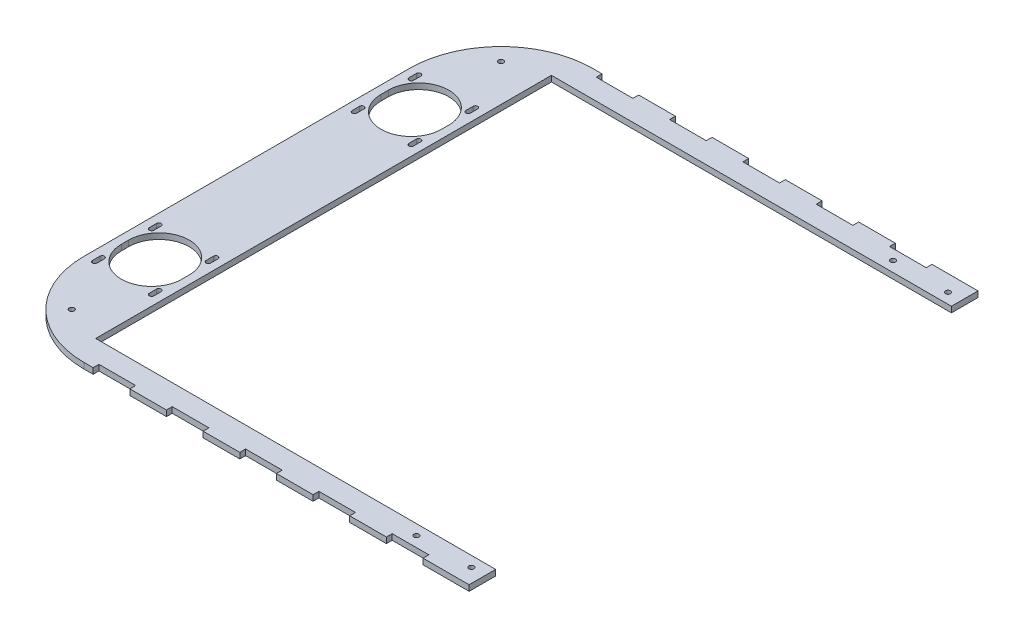
SolidWorks part; units mm, degrees
ref_plane "Front Plane" through (0, 0, 0) normal (0, 0, 1) x (1, 0, 0)
ref_plane "Top Plane" through (0, 0, 0) normal (0, 1, 0) x (1, 0, 0)
ref_plane "Right Plane" through (0, 0, 0) normal (1, 0, 0) x (0, 0, -1)
sketch "Sketch1" plane through (0, 11.0302, 0) normal (0, 1, 0) x (1, 0, 0)
  line L0 (-162.1567, -108.1674) -> (-194.8999, -108.1674) construction
  line L1 (-194.8999, 71.4826) -> (-162.1567, 71.4826) construction
  line L2 (-199.5283, 34.111) -> (-199.5283, 66.8542) construction
  line L3 (-157.5283, -142.1674) -> (-157.5283, 105.4826) construction
  line L4 (-162.1567, -108.1674) -> (-194.8999, -108.1674)
  line L5 (-194.8999, 71.4826) -> (-162.1567, 71.4826)
  line L6 (-199.5283, 34.111) -> (-199.5283, 66.8542)
  line L7 (-157.5283, -108.1674) -> (-157.5283, 71.4826)
  line L8 (-162.1567, 71.4826) -> (-157.5283, 71.4826)
  line L9 (-162.1567, -108.1674) -> (-157.5283, -108.1674)
  line L10 (-199.5283, 34.111) -> (-199.5283, -108.1674)
  line L11 (-199.5283, -108.1674) -> (-194.8999, -108.1674)
  line L12 (-194.8999, 71.4826) -> (-199.5283, 71.4826)
  line L13 (-199.5283, 66.8542) -> (-199.5283, 71.4826)
  circle A0 centre (-163.0283, 65.9826) radius 1.25 construction
  circle A1 centre (-163.0283, 34.9826) radius 1.25 construction
  circle A2 centre (-194.0283, 34.9826) radius 1.25 construction
  circle A3 centre (-194.0283, 65.9826) radius 1.25 construction
  circle A4 centre (-163.0283, -102.6674) radius 1.25 construction
  circle A5 centre (-163.0283, -71.6674) radius 1.25 construction
  circle A6 centre (-194.0283, -102.6674) radius 1.25 construction
  circle A7 centre (-194.0283, -71.6674) radius 1.25 construction
  circle A8 centre (-163.0283, 65.9826) radius 1.25
  circle A9 centre (-163.0283, 34.9826) radius 1.25
  circle A10 centre (-194.0283, 34.9826) radius 1.25
  circle A11 centre (-194.0283, 65.9826) radius 1.25
  circle A12 centre (-163.0283, -102.6674) radius 1.25
  circle A13 centre (-163.0283, -71.6674) radius 1.25
  circle A14 centre (-194.0283, -102.6674) radius 1.25
  circle A15 centre (-194.0283, -71.6674) radius 1.25
  circle A16 centre (-178.5283, -87.1674) radius 16.5 construction
  circle A17 centre (-178.5283, 50.4826) radius 16.5 construction
  circle A18 centre (-178.5283, -87.1674) radius 16.5
  circle A19 centre (-178.5283, 50.4826) radius 16.5
extrude "Boss-Extrude1" add sketch "Sketch1" along normal blind 3.15
sketch "Sketch2" plane through (0, 14.1802, 0) normal (0, 1, 0) x (1, 0, 0)
  line L0 (-157.5283, -142.1674) -> (-157.5283, 105.4826) construction
  line L1 (-157.5283, -142.1674) -> (-157.5283, 105.4826)
  line L2 (45.6717, -142.1674) -> (-157.5283, -142.1674) construction
  line L3 (45.6717, -142.1674) -> (-157.5283, -142.1674)
  line L4 (45.6717, 105.4826) -> (45.6717, -142.1674) construction
  line L5 (45.6717, 105.4826) -> (45.6717, -142.1674)
  line L6 (-157.5283, 105.4826) -> (45.6717, 105.4826) construction
  line L7 (-157.5283, 105.4826) -> (45.6717, 105.4826)
  line L8 (-199.5283, 71.4826) -> (-199.5283, -108.1674) construction
  line L9 (-199.5283, 71.4826) -> (-199.5283, -108.1674)
  line L10 (-199.5283, 71.4826) -> (-199.5283, 105.4826)
  line L11 (-199.5283, 105.4826) -> (-157.5283, 105.4826)
  line L12 (-199.5283, -108.1674) -> (-199.5283, -142.1674)
  line L13 (-199.5283, 120.4826) -> (-157.5283, 120.4826)
  line L14 (-157.5283, 120.4826) -> (60.6717, 120.4826)
  line L15 (60.6717, 120.4826) -> (60.6717, -157.1674)
  line L16 (60.6717, -157.1674) -> (-157.5283, -157.1674)
  line L17 (-157.5283, 107.4826) -> (45.6717, 107.4826)
  line L18 (45.6717, -144.1674) -> (-157.5283, -144.1674)
  line L19 (-157.5283, 105.4826) -> (-157.5283, 107.4826)
  line L20 (45.6717, 105.4826) -> (45.6717, 107.4826)
  line L21 (45.6717, -142.1674) -> (45.6717, -144.1674)
  line L22 (-157.5283, -142.1674) -> (-157.5283, -144.1674)
  line L23 (45.6717, 107.4826) -> (60.6717, 107.4826)
  line L24 (45.6717, -144.1674) -> (60.6717, -144.1674)
  line L25 (-157.5283, -157.1674) -> (-199.5283, -157.1674)
  line L26 (-199.5283, -157.1674) -> (-199.5283, -142.1674)
  line L27 (-199.5283, 120.4826) -> (-199.5283, 105.4826)
  line M10 (-199.5283, -108.1674) -> (-157.5283, -108.1674)
  line M12 (-157.5283, 71.4826) -> (-199.5283, 71.4826)
  dimension "D1" = 15
  dimension "D2" = 2
extrude "Boss-Extrude2" add sketch "Sketch2" against normal up to surface (3.15 mm away) contours L26 L25 L16 L15 L24 L18 L22 L1 L12 M10 | L11 L10 L1 M12 | L13 L27 L11 L19 L17 L23 L15 L14 up to face at (-178.5283, 11.0302, 18.3424)
fillet "Fillet1" radius 50 2 edges at (-199.5283, 12.6052, 157.1674) (-199.5283, 12.6052, -120.4826)
sketch "Sketch3" plane through (0, 14.1802, 0) normal (0, 1, 0) x (1, 0, 0)
  line L0 (55.5717, 120.4826) -> (-144.4283, 120.4826) construction
  line L1 (-104.4283, 120.4826) -> (-84.4283, 120.4826)
  line L2 (-144.4283, 120.4826) -> (-124.4283, 120.4826)
  line L3 (-144.4283, 120.4826) -> (-144.4283, 117.3226)
  line L4 (-144.4283, 117.3226) -> (-124.4283, 117.3226)
  line L5 (-124.4283, 120.4826) -> (-124.4283, 117.3226)
  line L6 (-144.4283, 120.4826) -> (-124.4283, 117.3226) construction
  line L7 (-144.4283, 117.3226) -> (-124.4283, 120.4826) construction
  line L8 (-84.4283, 120.4826) -> (-84.4283, 117.3226)
  line L9 (-104.4283, 117.3226) -> (-84.4283, 117.3226)
  line L10 (-104.4283, 120.4826) -> (-104.4283, 117.3226)
  line L11 (-64.4283, 120.4826) -> (-44.4283, 120.4826)
  line L12 (-44.4283, 120.4826) -> (-44.4283, 117.3226)
  line L13 (-64.4283, 117.3226) -> (-44.4283, 117.3226)
  line L14 (-64.4283, 120.4826) -> (-64.4283, 117.3226)
  line L15 (-24.4283, 120.4826) -> (-4.4283, 120.4826)
  line L16 (-4.4283, 120.4826) -> (-4.4283, 117.3226)
  line L17 (-24.4283, 117.3226) -> (-4.4283, 117.3226)
  line L18 (-24.4283, 120.4826) -> (-24.4283, 117.3226)
  line L19 (15.5717, 120.4826) -> (35.5717, 120.4826)
  line L20 (35.5717, 120.4826) -> (35.5717, 117.3226)
  line L21 (15.5717, 117.3226) -> (35.5717, 117.3226)
  line L22 (15.5717, 120.4826) -> (15.5717, 117.3226)
  line L23 (-199.5283, -18.3424) -> (55.5717, -18.3424) construction
  line L24 (-199.5283, 70.4826) -> (-199.5283, -107.1674) construction
  line L25 (15.5717, -157.1674) -> (15.5717, -154.0074)
  line L26 (-24.4283, -157.1674) -> (-24.4283, -154.0074)
  line L27 (-64.4283, -157.1674) -> (-64.4283, -154.0074)
  line L28 (-104.4283, -157.1674) -> (-104.4283, -154.0074)
  line L29 (-144.4283, -154.0074) -> (-124.4283, -157.1674) construction
  line L30 (-144.4283, -157.1674) -> (-124.4283, -154.0074) construction
  line L31 (-144.4283, -157.1674) -> (-144.4283, -154.0074)
  line L32 (55.5717, -157.1674) -> (-144.4283, -157.1674) construction
  line L33 (15.5717, -154.0074) -> (35.5717, -154.0074)
  line L34 (35.5717, -157.1674) -> (35.5717, -154.0074)
  line L35 (15.5717, -157.1674) -> (35.5717, -157.1674)
  line L36 (-24.4283, -154.0074) -> (-4.4283, -154.0074)
  line L37 (-4.4283, -157.1674) -> (-4.4283, -154.0074)
  line L38 (-24.4283, -157.1674) -> (-4.4283, -157.1674)
  line L39 (-64.4283, -154.0074) -> (-44.4283, -154.0074)
  line L40 (-44.4283, -157.1674) -> (-44.4283, -154.0074)
  line L41 (-64.4283, -157.1674) -> (-44.4283, -157.1674)
  line L42 (-104.4283, -154.0074) -> (-84.4283, -154.0074)
  line L43 (-84.4283, -157.1674) -> (-84.4283, -154.0074)
  line L44 (-124.4283, -157.1674) -> (-124.4283, -154.0074)
  line L45 (-144.4283, -154.0074) -> (-124.4283, -154.0074)
  line L46 (-144.4283, -157.1674) -> (-124.4283, -157.1674)
  line L47 (-104.4283, -157.1674) -> (-84.4283, -157.1674)
  point P7 (-134.4283, 118.9026)
  point P49 (-134.4283, -155.5874)
  dimension "D1" = 20
  dimension "D2" = 3.16
  dimension "D3" = 5
extrude "Cut-Extrude1" cut sketch "Sketch3" against normal through all
sketch "Sketch4" plane through (0, 14.1802, 0) normal (0, 1, 0) x (1, 0, 0)
  line L0 (-157.5283, -18.3424) -> (-199.5283, -18.3424) construction
  line L1 (-157.5283, -144.1674) -> (-157.5283, 107.4826) construction
  line L2 (-199.5283, 70.4826) -> (-199.5283, -107.1674) construction
  line L3 (-157.5283, 78.4826) -> (-184.8836, 105.838) construction
  line L4 (-157.5283, -144.1674) -> (-157.5283, 107.4826) construction
  circle A0 centre (-177.8126, 98.7669) radius 1.4
  circle A1 centre (-177.8126, -135.4517) radius 1.4
  dimension "D1" = 10
extrude "Cut-Extrude2" cut sketch "Sketch4" against normal blind 10
sketch "Sketch5" plane through (0, 14.1802, 0) normal (0, 1, 0) x (1, 0, 0)
  circle A1 centre (53.1217, -148.3424) radius 1.4 construction
  circle A2 centre (53.1217, 111.6476) radius 1.4
  circle A3 centre (53.1217, -148.3424) radius 1.4
  circle A5 centre (23.1217, 111.6476) radius 1.4
  circle A6 centre (23.1217, -148.3424) radius 1.4 construction
  circle A7 centre (23.1217, -148.3424) radius 1.4
  circle A10 centre (53.1217, 111.6476) radius 1.4 construction
  circle A11 centre (23.1217, 111.6476) radius 1.4 construction
extrude "Cut-Extrude3" cut sketch "Sketch5" against normal blind 10
sketch "Sketch6" plane through (0, 14.1802, 0) normal (0, 1, 0) x (1, 0, 0)
  line L0 (-161.7783, 69.9826) -> (-161.7783, 65.9826)
  line L1 (-164.2783, 65.9826) -> (-164.2783, 69.9826)
  line L2 (-161.7783, 38.9826) -> (-161.7783, 34.9826)
  line L3 (-164.2783, 34.9826) -> (-164.2783, 38.9826)
  line L4 (-192.7783, 38.9826) -> (-192.7783, 34.9826)
  line L5 (-195.2783, 34.9826) -> (-195.2783, 38.9826)
  line L6 (-195.2783, 69.9826) -> (-195.2783, 65.9826)
  line L7 (-192.7783, 69.9826) -> (-192.7783, 65.9826)
  line L8 (-162.0283, 54.4826) -> (-162.0283, 50.4826)
  line L9 (-195.0283, 54.4826) -> (-195.0283, 50.4826)
  line L10 (-157.5283, -18.3424) -> (-199.5283, -18.3424) construction
  line L11 (-195.0283, -91.1674) -> (-195.0283, -87.1674)
  line L12 (-162.0283, -91.1674) -> (-162.0283, -87.1674)
  line L13 (-192.7783, -106.6674) -> (-192.7783, -102.6674)
  line L14 (-195.2783, -106.6674) -> (-195.2783, -102.6674)
  line L15 (-195.2783, -71.6674) -> (-195.2783, -75.6674)
  line L16 (-192.7783, -75.6674) -> (-192.7783, -71.6674)
  line L17 (-164.2783, -71.6674) -> (-164.2783, -75.6674)
  line L18 (-161.7783, -75.6674) -> (-161.7783, -71.6674)
  line L19 (-164.2783, -102.6674) -> (-164.2783, -106.6674)
  line L20 (-161.7783, -106.6674) -> (-161.7783, -102.6674)
  line L48 (-104.4283, 117.3226) -> (-104.4283, 120.4826)
  line L49 (-104.4283, 120.4826) -> (-124.4283, 120.4826)
  line L50 (-124.4283, 120.4826) -> (-124.4283, 117.3226)
  line L51 (-124.4283, 117.3226) -> (-144.4283, 117.3226)
  line L52 (-144.4283, 117.3226) -> (-144.4283, 120.4826)
  line L53 (-144.4283, 120.4826) -> (-149.5283, 120.4826)
  line L54 (-199.5283, 70.4826) -> (-199.5283, -107.1674)
  line L55 (-149.5283, -157.1674) -> (-144.4283, -157.1674)
  line L56 (-144.4283, -157.1674) -> (-144.4283, -154.0074)
  line L57 (-144.4283, -154.0074) -> (-124.4283, -154.0074)
  line L58 (-124.4283, -154.0074) -> (-124.4283, -157.1674)
  line L59 (-124.4283, -157.1674) -> (-104.4283, -157.1674)
  line L60 (-104.4283, -157.1674) -> (-104.4283, -154.0074)
  line L61 (-104.4283, -154.0074) -> (-84.4283, -154.0074)
  line L62 (-84.4283, -154.0074) -> (-84.4283, -157.1674)
  line L63 (-84.4283, -157.1674) -> (-64.4283, -157.1674)
  line L64 (-64.4283, -157.1674) -> (-64.4283, -154.0074)
  line L65 (-64.4283, -154.0074) -> (-44.4283, -154.0074)
  line L66 (-44.4283, -154.0074) -> (-44.4283, -157.1674)
  line L67 (-44.4283, -157.1674) -> (-24.4283, -157.1674)
  line L68 (-24.4283, -157.1674) -> (-24.4283, -154.0074)
  line L69 (-24.4283, -154.0074) -> (-4.4283, -154.0074)
  line L70 (-4.4283, -154.0074) -> (-4.4283, -157.1674)
  line L71 (-4.4283, -157.1674) -> (15.5717, -157.1674)
  line L72 (15.5717, -157.1674) -> (15.5717, -154.0074)
  line L73 (15.5717, -154.0074) -> (35.5717, -154.0074)
  line L74 (35.5717, -154.0074) -> (35.5717, -157.1674)
  line L75 (35.5717, -157.1674) -> (60.6717, -157.1674)
  line L76 (60.6717, -157.1674) -> (60.6717, -144.1674)
  line L77 (60.6717, -144.1674) -> (-157.5283, -144.1674)
  line L78 (-157.5283, -144.1674) -> (-157.5283, 107.4826)
  line L79 (-157.5283, 107.4826) -> (60.6717, 107.4826)
  line L80 (60.6717, 107.4826) -> (60.6717, 120.4826)
  line L81 (60.6717, 120.4826) -> (35.5717, 120.4826)
  line L82 (35.5717, 120.4826) -> (35.5717, 117.3226)
  line L83 (35.5717, 117.3226) -> (15.5717, 117.3226)
  line L84 (15.5717, 117.3226) -> (15.5717, 120.4826)
  line L85 (15.5717, 120.4826) -> (-4.4283, 120.4826)
  line L86 (-4.4283, 120.4826) -> (-4.4283, 117.3226)
  line L87 (-4.4283, 117.3226) -> (-24.4283, 117.3226)
  line L88 (-24.4283, 117.3226) -> (-24.4283, 120.4826)
  line L89 (-24.4283, 120.4826) -> (-44.4283, 120.4826)
  line L90 (-44.4283, 120.4826) -> (-44.4283, 117.3226)
  line L91 (-44.4283, 117.3226) -> (-64.4283, 117.3226)
  line L92 (-64.4283, 117.3226) -> (-64.4283, 120.4826)
  line L93 (-64.4283, 120.4826) -> (-84.4283, 120.4826)
  line L94 (-84.4283, 120.4826) -> (-84.4283, 117.3226)
  line L95 (-84.4283, 117.3226) -> (-104.4283, 117.3226)
  line L96 (-104.4283, 117.3226) -> (-104.4283, 120.4826)
  line L97 (-104.4283, 120.4826) -> (-124.4283, 120.4826)
  line L98 (-124.4283, 120.4826) -> (-124.4283, 117.3226)
  line L99 (-124.4283, 117.3226) -> (-144.4283, 117.3226)
  line L100 (-144.4283, 117.3226) -> (-144.4283, 120.4826)
  line L101 (-144.4283, 120.4826) -> (-149.5283, 120.4826)
  line L102 (-199.5283, 70.4826) -> (-199.5283, -107.1674)
  line L103 (-149.5283, -157.1674) -> (-144.4283, -157.1674)
  line L104 (-144.4283, -157.1674) -> (-144.4283, -154.0074)
  line L105 (-144.4283, -154.0074) -> (-124.4283, -154.0074)
  line L106 (-124.4283, -154.0074) -> (-124.4283, -157.1674)
  line L107 (-124.4283, -157.1674) -> (-104.4283, -157.1674)
  line L108 (-104.4283, -157.1674) -> (-104.4283, -154.0074)
  line L109 (-104.4283, -154.0074) -> (-84.4283, -154.0074)
  line L110 (-84.4283, -154.0074) -> (-84.4283, -157.1674)
  line L111 (-84.4283, -157.1674) -> (-64.4283, -157.1674)
  line L112 (-64.4283, -157.1674) -> (-64.4283, -154.0074)
  line L113 (-64.4283, -154.0074) -> (-44.4283, -154.0074)
  line L114 (-44.4283, -154.0074) -> (-44.4283, -157.1674)
  line L115 (-44.4283, -157.1674) -> (-24.4283, -157.1674)
  line L116 (-24.4283, -157.1674) -> (-24.4283, -154.0074)
  line L117 (-24.4283, -154.0074) -> (-4.4283, -154.0074)
  line L118 (-4.4283, -154.0074) -> (-4.4283, -157.1674)
  line L119 (-4.4283, -157.1674) -> (15.5717, -157.1674)
  line L120 (15.5717, -157.1674) -> (15.5717, -154.0074)
  line L121 (15.5717, -154.0074) -> (35.5717, -154.0074)
  line L122 (35.5717, -154.0074) -> (35.5717, -157.1674)
  line L123 (35.5717, -157.1674) -> (60.6717, -157.1674)
  line L124 (60.6717, -157.1674) -> (60.6717, -144.1674)
  line L125 (60.6717, -144.1674) -> (-157.5283, -144.1674)
  line L126 (-157.5283, -144.1674) -> (-157.5283, 107.4826)
  line L127 (-157.5283, 107.4826) -> (60.6717, 107.4826)
  line L128 (60.6717, 107.4826) -> (60.6717, 120.4826)
  line L129 (60.6717, 120.4826) -> (35.5717, 120.4826)
  line L130 (35.5717, 120.4826) -> (35.5717, 117.3226)
  line L131 (35.5717, 117.3226) -> (15.5717, 117.3226)
  line L132 (15.5717, 117.3226) -> (15.5717, 120.4826)
  line L133 (15.5717, 120.4826) -> (-4.4283, 120.4826)
  line L134 (-4.4283, 120.4826) -> (-4.4283, 117.3226)
  line L135 (-4.4283, 117.3226) -> (-24.4283, 117.3226)
  line L136 (-24.4283, 117.3226) -> (-24.4283, 120.4826)
  line L137 (-24.4283, 120.4826) -> (-44.4283, 120.4826)
  line L138 (-44.4283, 120.4826) -> (-44.4283, 117.3226)
  line L139 (-44.4283, 117.3226) -> (-64.4283, 117.3226)
  line L140 (-64.4283, 117.3226) -> (-64.4283, 120.4826)
  line L141 (-64.4283, 120.4826) -> (-84.4283, 120.4826)
  line L142 (-84.4283, 120.4826) -> (-84.4283, 117.3226)
  line L143 (-84.4283, 117.3226) -> (-104.4283, 117.3226)
  arc A0 (-195.2783, 65.9826) -> (-192.7783, 65.9826) centre (-194.0283, 65.9826) ccw
  arc A2 (-149.5283, 120.4826) -> (-199.5283, 70.4826) centre (-149.5283, 70.4826) ccw
  arc A3 (-199.5283, -107.1674) -> (-149.5283, -157.1674) centre (-149.5283, -107.1674) ccw
  arc A4 (-149.5283, 120.4826) -> (-199.5283, 70.4826) centre (-149.5283, 70.4826) ccw
  arc A5 (-199.5283, -107.1674) -> (-149.5283, -157.1674) centre (-149.5283, -107.1674) ccw
  arc A6 (-162.0283, 54.4826) -> (-195.0283, 54.4826) centre (-178.5283, 54.4826) ccw
  arc A7 (-195.2783, -71.6674) -> (-192.7783, -71.6674) centre (-194.0283, -71.6674) cw
  arc A8 (-164.2783, -71.6674) -> (-161.7783, -71.6674) centre (-163.0283, -71.6674) cw
  arc A9 (-164.2783, -102.6674) -> (-161.7783, -102.6674) centre (-163.0283, -102.6674) cw
  arc A10 (-195.0283, -87.1674) -> (-162.0283, -87.1674) centre (-178.5283, -87.1674) cw
  arc A12 (-192.7783, 69.9826) -> (-195.2783, 69.9826) centre (-194.0283, 69.9826) ccw
  arc A14 (-161.7783, 38.9826) -> (-164.2783, 38.9826) centre (-163.0283, 38.9826) ccw
  arc A16 (-161.7783, 69.9826) -> (-164.2783, 69.9826) centre (-163.0283, 69.9826) ccw
  arc A18 (-192.7783, 38.9826) -> (-195.2783, 38.9826) centre (-194.0283, 38.9826) ccw
  arc A19 (-192.7783, -75.6674) -> (-195.2783, -75.6674) centre (-194.0283, -75.6674) cw
  arc A20 (-161.7783, -106.6674) -> (-164.2783, -106.6674) centre (-163.0283, -106.6674) cw
  arc A21 (-161.7783, -75.6674) -> (-164.2783, -75.6674) centre (-163.0283, -75.6674) cw
  arc A22 (-192.7783, -106.6674) -> (-195.2783, -106.6674) centre (-194.0283, -106.6674) cw
  arc A23 (-162.0283, -91.1674) -> (-195.0283, -91.1674) centre (-178.5283, -91.1674) cw
  arc A24 (-195.2783, -102.6674) -> (-192.7783, -102.6674) centre (-194.0283, -102.6674) cw
  circle A25 centre (-177.8126, 98.7669) radius 1.4
  circle A26 centre (-177.8126, 98.7669) radius 1.4
  circle A27 centre (-177.8126, -135.4517) radius 1.4
  circle A28 centre (-177.8126, -135.4517) radius 1.4
  circle A29 centre (53.1217, 111.6476) radius 1.4
  circle A30 centre (53.1217, 111.6476) radius 1.4
  circle A31 centre (53.1217, -148.3424) radius 1.4
  circle A32 centre (53.1217, -148.3424) radius 1.4
  arc A33 (-195.0283, 50.4826) -> (-162.0283, 50.4826) centre (-178.5283, 50.4826) ccw
  arc A34 (-164.2783, 65.9826) -> (-161.7783, 65.9826) centre (-163.0283, 65.9826) ccw
  arc A35 (-164.2783, 34.9826) -> (-161.7783, 34.9826) centre (-163.0283, 34.9826) ccw
  arc A36 (-195.2783, 34.9826) -> (-192.7783, 34.9826) centre (-194.0283, 34.9826) ccw
  point P54 (-194.0283, 34.9826)
  point P63 (-163.0283, 34.9826)
  point P70 (-163.0283, 65.9826)
  dimension "D2" = 4
  dimension "D3" = 4
  dimension "D4" = 4
  dimension "D5" = 4
  dimension "D1" = 0
  dimension "D12" = 0
  dimension "D13" = 0
  dimension "D14" = 0
  dimension "D15" = 0
extrude "Cut-Extrude4" cut sketch "Sketch6" against normal through all contours L6 A0 L7 A12 | A6 L9 A33 L8 | L5 A18 L4 A36 | L3 A14 L2 A35 | L1 A16 L0 A34 | A23 L11 A10 L12 | L14 A24 L13 A22 | L15 A19 L16 A7 | L17 A21 L18 A8 | L19 A20 L20 A9
sketch "Sketch8" plane through (0, 14.1802, 0) normal (0, 1, 0) x (1, 0, 0)
  line L0 (60.6717, -144.1674) -> (-157.5283, -144.1674) construction
  line L1 (-157.5283, 107.4826) -> (60.6717, 107.4826) construction
  line L2 (60.6717, -144.1674) -> (-157.5283, -144.1674)
  line L3 (-157.5283, 107.4826) -> (60.6717, 107.4826)
  line L4 (-157.5283, 105.9826) -> (60.6717, 105.9826)
  line L5 (60.6717, -142.6674) -> (-157.5283, -142.6674)
  line L6 (-157.5283, 107.4826) -> (-157.5283, 105.9826)
  line L7 (60.6717, 107.4826) -> (60.6717, 105.9826)
  line L8 (60.6717, -144.1674) -> (60.6717, -142.6674)
  line L9 (-157.5283, -144.1674) -> (-157.5283, -142.6674)
  dimension "D1" = 1.5
extrude "Boss-Extrude3" add sketch "Sketch8" against normal up to surface (3.15 mm away) up to face at (-163.0283, 11.0302, -36.9826)
